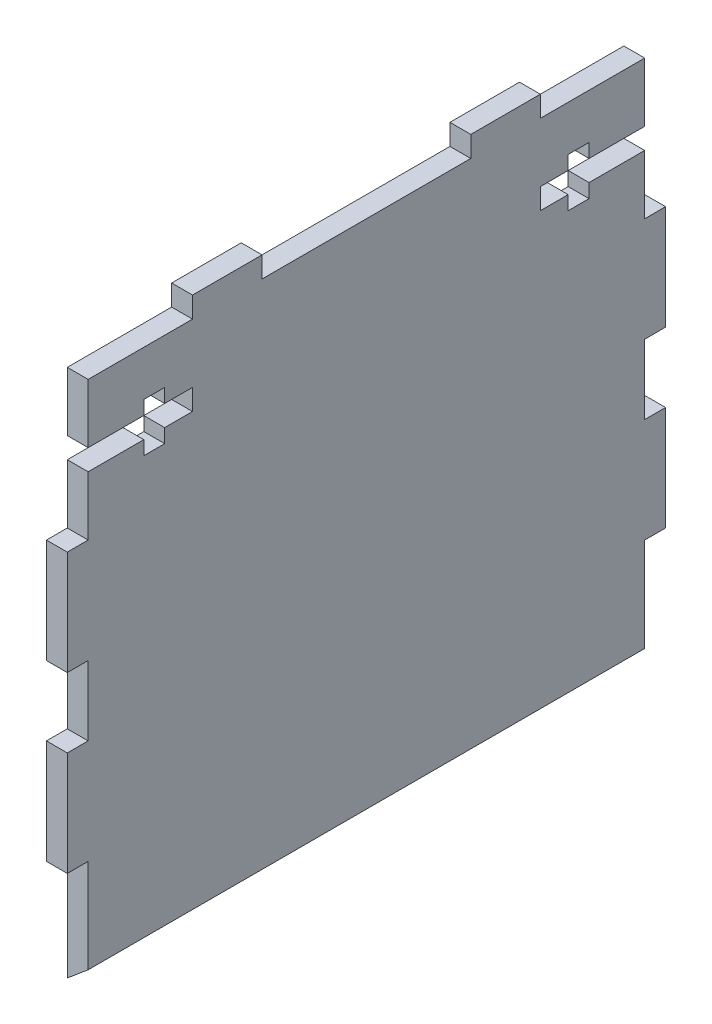
SolidWorks part; units mm, degrees
ref_plane "Front" through (0, 0, 0) normal (0, 0, 1) x (1, 0, 0)
ref_plane "Top" through (0, 0, 0) normal (0, 1, 0) x (1, 0, 0)
ref_plane "Right" through (0, 0, 0) normal (1, 0, 0) x (0, 0, -1)
sketch "Croquis1" plane through (0, 0, 0) normal (0, 0, 1) x (1, 0, 0)
  line L1 (3, 0) -> (3, -63.5)
  line L2 (3, -63.5) -> (0, -66.0173)
  line L3 (0, -66.0173) -> (0, 0)
  line L4 (0, -66.0173) -> (14.6405, -66.0173) construction
  line L7 (0, 0) -> (0, 10)
  line L8 (0, 10) -> (3, 10)
  line L9 (3, 0) -> (3, 10)
  line L10 (0, 0) -> (3, 10) construction
  line L11 (0, 10) -> (3, 0) construction
  point P8 (1.5, 5)
  dimension "D1" = 3
  dimension "D2" = 63.5
  dimension "D3" = 40
  dimension "D4" = 10
extrude "Saliente-Extruir1" add sketch "Croquis1" along normal blind 80
sketch "Croquis2" plane through (0, 0, 80) normal (0, 0, 1) x (1, 0, 0)
  line L0 (0, 10) -> (0, -66.0173) construction
  line L1 (0, -10) -> (3, -10)
  line L2 (0, -10) -> (0, -25)
  line L3 (0, -25) -> (3, -25)
  line L4 (3, -10) -> (3, -25)
  line L5 (0, -10) -> (3, -25) construction
  line L6 (0, -25) -> (3, -10) construction
  line L7 (3, -63.5) -> (3, 10) construction
  line L9 (0, -35) -> (3, -35)
  line L10 (0, -35) -> (0, -50)
  line L11 (0, -50) -> (3, -50)
  line L12 (3, -35) -> (3, -50)
  line L13 (0, -35) -> (3, -50) construction
  line L14 (0, -50) -> (3, -35) construction
  point P4 (1.5, -17.5)
  point P13 (1.5, -42.5)
  dimension "D1" = 10
  dimension "D2" = 15
  dimension "D3" = 10
  dimension "D4" = 15
extrude "Saliente-Extruir2" add sketch "Croquis2" along normal blind 3
sketch "Croquis3" plane through (0, 0, 0) normal (0, 0, -1) x (-1, 0, 0)
  line L0 (-3, -63.5) -> (-3, 10) construction
  line L1 (-3, -10) -> (0, -10)
  line L2 (-3, -10) -> (-3, -25)
  line L3 (-3, -25) -> (0, -25)
  line L4 (0, -10) -> (0, -25)
  line L5 (-3, -10) -> (0, -25) construction
  line L6 (-3, -25) -> (0, -10) construction
  line L7 (0, 10) -> (0, -66.0173) construction
  line L9 (-3, -35) -> (0, -35)
  line L10 (-3, -35) -> (-3, -50)
  line L11 (-3, -50) -> (0, -50)
  line L12 (0, -35) -> (0, -50)
  line L13 (-3, -35) -> (0, -50) construction
  line L14 (-3, -50) -> (0, -35) construction
  point P4 (-1.5, -17.5)
  point P13 (-1.5, -42.5)
  dimension "D1" = 10
  dimension "D2" = 15
  dimension "D3" = 10
  dimension "D4" = 15
extrude "Saliente-Extruir3" add sketch "Croquis3" along normal blind 3
sketch "Croquis4" plane through (0, 0, 0) normal (-1, 0, 0) x (0, 0, 1)
  line L0 (0, 1.5) -> (8, 1.5)
  line L1 (0, 1.5) -> (0, -1.5)
  line L2 (0, -1.5) -> (8, -1.5)
  line L3 (15, 1.5) -> (15, -1.5)
  line L4 (8, -1.5) -> (8, -3.5)
  line L5 (11, 1.5) -> (15, 1.5)
  line L6 (11, -1.5) -> (11, -3.5)
  line L7 (11, 3.5) -> (8, 3.5)
  line L8 (11, 3.5) -> (11, 1.5)
  line L9 (11, -3.5) -> (8, -3.5)
  line L10 (8, 3.5) -> (8, 1.5)
  line L11 (11, -1.5) -> (15, -1.5)
  line L12 (0, 10) -> (0, -10) construction
  line L13 (15, 0) -> (0, 0) construction
  line L14 (80, 10) -> (0, 10) construction
  line L15 (40, 10) -> (40, -53.1764) construction
  line L16 (65, 0) -> (80, 0) construction
  line L17 (69, -1.5) -> (65, -1.5)
  line L18 (72, 3.5) -> (72, 1.5)
  line L19 (69, -3.5) -> (72, -3.5)
  line L20 (69, 3.5) -> (69, 1.5)
  line L21 (69, 3.5) -> (72, 3.5)
  line L22 (69, -1.5) -> (69, -3.5)
  line L23 (69, 1.5) -> (65, 1.5)
  line L24 (72, -1.5) -> (72, -3.5)
  line L25 (65, 1.5) -> (65, -1.5)
  line L26 (80, -1.5) -> (72, -1.5)
  line L27 (80, 1.5) -> (80, -1.5)
  line L28 (80, 1.5) -> (72, 1.5)
  dimension "D1" = 8
  dimension "D2" = 3
  dimension "D3" = 7
  dimension "D4" = 10
  dimension "D5" = 3
  dimension "D6" = 3.5
  dimension "D7" = 15
extrude "Cortar-Extruir1" cut sketch "Croquis4" against normal blind 10
sketch "Croquis5" plane through (0, 0, 0) normal (-1, 0, 0) x (0, 0, 1)
  line L0 (80, 10) -> (0, 10) construction
  line L1 (15, 10) -> (25, 10)
  line L2 (15, 10) -> (15, 13)
  line L3 (15, 13) -> (25, 13)
  line L4 (25, 10) -> (25, 13)
  line L5 (15, 10) -> (25, 13) construction
  line L6 (15, 13) -> (25, 10) construction
  line L7 (40, 10) -> (40, -10.6794) construction
  line L8 (65, 13) -> (55, 10) construction
  line L9 (65, 10) -> (55, 13) construction
  line L10 (55, 10) -> (55, 13)
  line L11 (65, 13) -> (55, 13)
  line L12 (65, 10) -> (65, 13)
  line L13 (65, 10) -> (55, 10)
  point P4 (20, 11.5)
  point P13 (60, 11.5)
  dimension "D1" = 3
  dimension "D2" = 15
  dimension "D3" = 10
extrude "Saliente-Extruir4" add sketch "Croquis5" against normal blind 3
